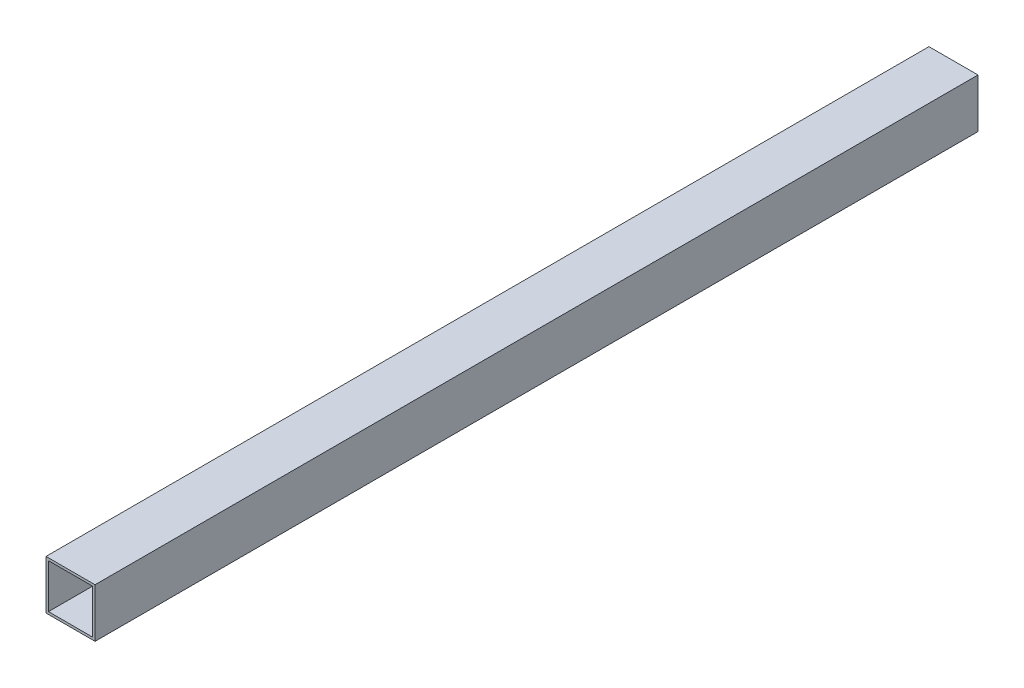
SolidWorks part; units mm, degrees
ref_plane "Front Plane" through (0, 0, 0) normal (0, 0, 1) x (1, 0, 0)
ref_plane "Top Plane" through (0, 0, 0) normal (0, 1, 0) x (1, 0, 0)
ref_plane "Right Plane" through (0, 0, 0) normal (1, 0, 0) x (0, 0, -1)
sketch "Sketch1" plane through (0, 0, 0) normal (0, 0, 1) x (1, 0, 0)
  line L1 (0, 0) -> (20, 0)
  line L2 (0, 0) -> (0, -20)
  line L3 (0, -20) -> (20, -20)
  line L4 (20, 0) -> (20, -20)
  line L5 (1, -19) -> (19, -19)
  line L6 (1, -19) -> (1, -1)
  line L7 (1, -1) -> (19, -1)
  line L8 (19, -19) -> (19, -1)
  line L9 (1, -19) -> (19, -1) construction
  line L10 (1, -1) -> (19, -19) construction
  point P5 (10, -10)
  dimension "D1" = 20
  dimension "D2" = 20
  dimension "D3" = 1
  dimension "D4" = 1
  dimension "D5" = 1
  dimension "D6" = 1
extrude "Boss-Extrude1" add sketch "Sketch1" along normal blind 360
ref_plane "Plane1" through (0, 0, 180) normal (0, 0, 1) x (1, 0, 0)
